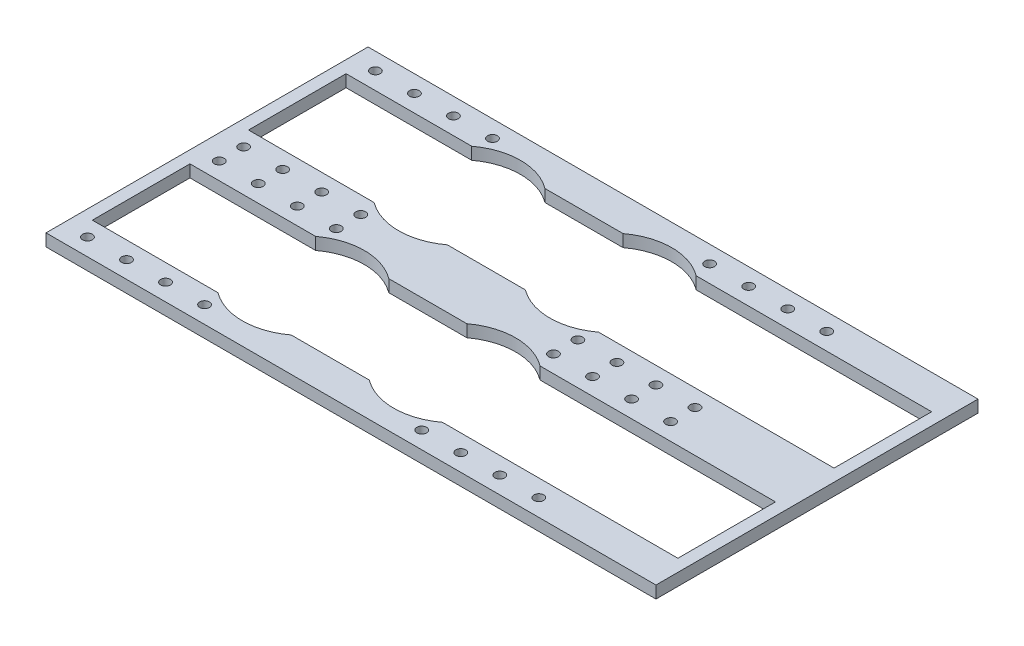
SolidWorks part; units mm, degrees
ref_plane "Front Plane" through (0, 0, 0) normal (0, 0, 1) x (1, 0, 0)
ref_plane "Top Plane" through (0, 0, 0) normal (0, 1, 0) x (1, 0, 0)
ref_plane "Right Plane" through (0, 0, 0) normal (1, 0, 0) x (0, 0, -1)
sketch "Sketch1" plane through (0, 0, 0) normal (0, 1, 0) x (1, 0, 0)
  line L1 (-80, 33) -> (80, 33)
  line L2 (-80, 33) -> (-80, -33)
  line L3 (-80, -33) -> (80, -33)
  line L4 (80, 33) -> (80, -33)
  line L5 (-80, 33) -> (80, -33) construction
  line L6 (-80, -33) -> (80, 33) construction
  point P0 (0, 0)
  dimension "D1" = 160
  dimension "D2" = 66
extrude "Boss-Extrude1" add sketch "Sketch1" along normal blind 40
sketch "Sketch2" plane through (0, 0, 33) normal (0, 0, 1) x (1, 0, 0)
  line L0 (80, 40) -> (80, 0) construction
  line L1 (-80, 40) -> (80, 40) construction
  line L2 (-80, 40) -> (50, 40)
  line L3 (-80, 40) -> (-80, 2.5)
  line L4 (-80, 2.5) -> (50, 2.5)
  line L5 (50, 40) -> (50, 2.5)
  line L6 (-80, 40) -> (50, 2.5) construction
  line L7 (-80, 2.5) -> (50, 40) construction
  line L8 (-80, 40) -> (-80, 0) construction
  circle A0 centre (70, 20) radius 4.025
  point P4 (80, 20)
  point P5 (-15, 21.25)
  dimension "D1" = 8.05
  dimension "D2" = 10
  dimension "D3" = 37.5
  dimension "D4" = 130
extrude "Cut-Extrude1" cut sketch "Sketch2" against normal through all
sketch "Sketch3" plane through (0, 40, 0) normal (0, 1, 0) x (1, 0, 0)
  line L0 (-80, 33) -> (-80, -33) construction
  line L1 (80, 33) -> (50, 33) construction
  line L2 (-75, 29.5) -> (-67, 29.5) construction
  line L3 (-75, 2.5) -> (-67, 2.5) construction
  line L4 (0, 0) -> (13.7346, 0) construction
  line L5 (-80, 33) -> (-80, -33) construction
  line L6 (-6.5, 29.5) -> (1.5, 29.5) construction
  line L7 (-75, 29.5) -> (-75, 2.5) construction
  line L8 (-77.5, 26) -> (42.5, 26)
  line L9 (-77.5, 26) -> (-77.5, 6)
  line L10 (-77.5, 6) -> (42.5, 6)
  line L11 (42.5, 26) -> (42.5, 6)
  line L12 (-6.5, 2.5) -> (1.5, 2.5) construction
  line L13 (-6.5, -2.5) -> (1.5, -2.5) construction
  line L14 (-75, -29.5) -> (-75, -2.5) construction
  line L15 (-6.5, -29.5) -> (1.5, -29.5) construction
  line L16 (-75, -2.5) -> (-67, -2.5) construction
  line L17 (-75, -29.5) -> (-67, -29.5) construction
  line L18 (42.5, -26) -> (42.5, -6)
  line L19 (-77.5, -6) -> (42.5, -6)
  line L20 (-77.5, -26) -> (-77.5, -6)
  line L21 (-77.5, -26) -> (42.5, -26)
  circle A0 centre (-75, 29.5) radius 1
  circle A1 centre (-75, 2.5) radius 1
  circle A2 centre (-67, 29.5) radius 1
  circle A3 centre (-59, 29.5) radius 1
  circle A4 centre (-51, 29.5) radius 1
  circle A11 centre (-67, 2.5) radius 1
  circle A12 centre (-59, 2.5) radius 1
  circle A13 centre (-51, 2.5) radius 1
  circle A50 centre (-6.5, 29.5) radius 1
  circle A51 centre (-6.5, 2.5) radius 1
  circle A52 centre (1.5, 29.5) radius 1
  circle A53 centre (9.5, 29.5) radius 1
  circle A54 centre (17.5, 29.5) radius 1
  circle A55 centre (1.5, 2.5) radius 1
  circle A56 centre (9.5, 2.5) radius 1
  circle A57 centre (17.5, 2.5) radius 1
  circle A58 centre (17.5, -2.5) radius 1
  circle A59 centre (9.5, -2.5) radius 1
  circle A60 centre (1.5, -2.5) radius 1
  circle A61 centre (17.5, -29.5) radius 1
  circle A62 centre (9.5, -29.5) radius 1
  circle A63 centre (1.5, -29.5) radius 1
  circle A64 centre (-6.5, -2.5) radius 1
  circle A65 centre (-6.5, -29.5) radius 1
  circle A66 centre (-51, -2.5) radius 1
  circle A67 centre (-59, -2.5) radius 1
  circle A68 centre (-67, -2.5) radius 1
  circle A69 centre (-51, -29.5) radius 1
  circle A70 centre (-59, -29.5) radius 1
  circle A71 centre (-67, -29.5) radius 1
  circle A72 centre (-75, -2.5) radius 1
  circle A73 centre (-75, -29.5) radius 1
  point P96 (-77.5, 16)
  point P97 (-75, 16)
  dimension "D1" = 2
  dimension "D3" = 3.5
  dimension "D4" = 27
  dimension "D12" = 2
  dimension "D2" = 5
  dimension "D6" = 8
  dimension "D8" = 8
  dimension "D9" = 20
  dimension "D10" = 120
  dimension "D11" = 2.5
  dimension "D13" = 44.5
  dimension "D15" = 8
  dimension "D17" = 8
  dimension "D5" = 4
  dimension "D7" = 4
  dimension "D14" = 4
  dimension "D16" = 4
extrude "Cut-Extrude2" cut sketch "Sketch3" against normal through all
sketch "Sketch4" plane through (0, 2.5, 0) normal (0, 1, 0) x (1, 0, 0)
  line L1 (-77.5, -6) -> (42.5, -6) construction
  line L2 (-77.5, 26) -> (42.5, 26) construction
  circle A0 centre (-44.25, -16) radius 12.5
  circle A1 centre (-51, -2.5) radius 1 construction
  circle A2 centre (-44.25, 16) radius 12.5
  circle A3 centre (-13.25, 16) radius 12.5
  circle A4 centre (-13.25, -16) radius 12.5
  circle A5 centre (-6.5, -2.5) radius 1 construction
  dimension "D1" = 25
  dimension "D4" = 6.75
  dimension "D2" = 6.75
  dimension "D3" = 10
  dimension "D5" = 10
extrude "Cut-Extrude3" cut sketch "Sketch4" against normal through all
sketch "Sketch5" plane through (0, 40, 0) normal (0, 1, 0) x (1, 0, 0)
  line L0 (80, 33) -> (50, 33) construction
  line L1 (45, 33) -> (80, 33)
  line L2 (45, 33) -> (45, -33)
  line L3 (45, -33) -> (80, -33)
  line L4 (80, 33) -> (80, -33)
  line L5 (45, 33) -> (80, -33) construction
  line L6 (45, -33) -> (80, 33) construction
  line L7 (42.5, -6) -> (42.5, -26) construction
  point P0 (62.5, 0)
  dimension "D1" = 2.5
extrude "Cut-Extrude5" cut sketch "Sketch5" against normal through all
